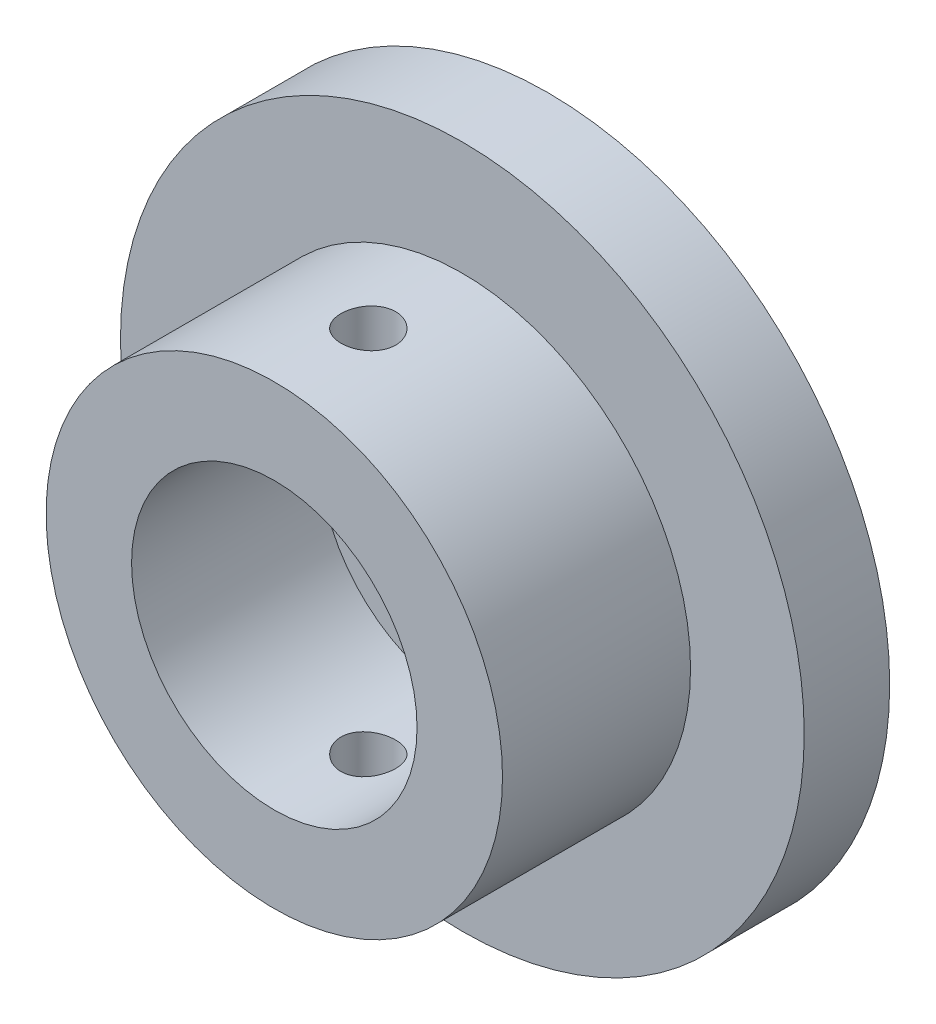
SolidWorks part; units mm, degrees
ref_plane "Alzado" through (0, 0, 0) normal (0, 0, 1) x (1, 0, 0)
ref_plane "Planta" through (0, 0, 0) normal (0, 1, 0) x (1, 0, 0)
ref_plane "Vista lateral" through (0, 0, 0) normal (1, 0, 0) x (0, 0, -1)
sketch "Croquis1" plane through (0, 0, 0) normal (0, 0, 1) x (1, 0, 0)
  circle A0 centre (0, 0) radius 20
  dimension "D1" = 40
extrude "Saliente-Extruir1" add sketch "Croquis1" along normal blind 5
sketch "Croquis2" plane through (0, 0, 5) normal (0, 0, 1) x (1, 0, 0)
  circle A0 centre (0, 0) radius 13.35
  circle A1 centre (0, 0) radius 8.35
  dimension "D2" = 16.7
  dimension "D1" = 5
extrude "Saliente-Extruir2" add sketch "Croquis2" along normal blind 11
sketch "Croquis3" plane through (0, 0, 0) normal (0, 1, 0) x (1, 0, 0)
  line L0 (-13.35, -16) -> (13.35, -16) construction
  line L1 (0, 0) -> (0, -10.5) construction
  circle A0 centre (0, -10.5) radius 1.6
  dimension "D1" = 3.2
  dimension "D2" = 5.5
extrude "Cortar-Extruir1" cut sketch "Croquis3" against normal mid plane 40
sketch "Croquis4" plane through (0, 0, 0) normal (0, 0, -1) x (-1, 0, 0)
  line L1 (-7.5, -10.5) -> (7.5, -10.5) construction
  line L2 (-7.5, -10.5) -> (-7.5, 10.5) construction
  line L3 (-7.5, 10.5) -> (7.5, 10.5) construction
  line L4 (7.5, -10.5) -> (7.5, 10.5) construction
  line L5 (-7.5, -10.5) -> (7.5, 10.5) construction
  line L6 (-7.5, 10.5) -> (7.5, -10.5) construction
  circle A0 centre (0, 0) radius 10 construction
  circle A1 centre (0, 0) radius 12.9035
  dimension "D1" = 20
  dimension "D2" = 15
  dimension "D3" = 21
extrude "Cortar-Extruir3" cut sketch "Croquis4" against normal blind 1
